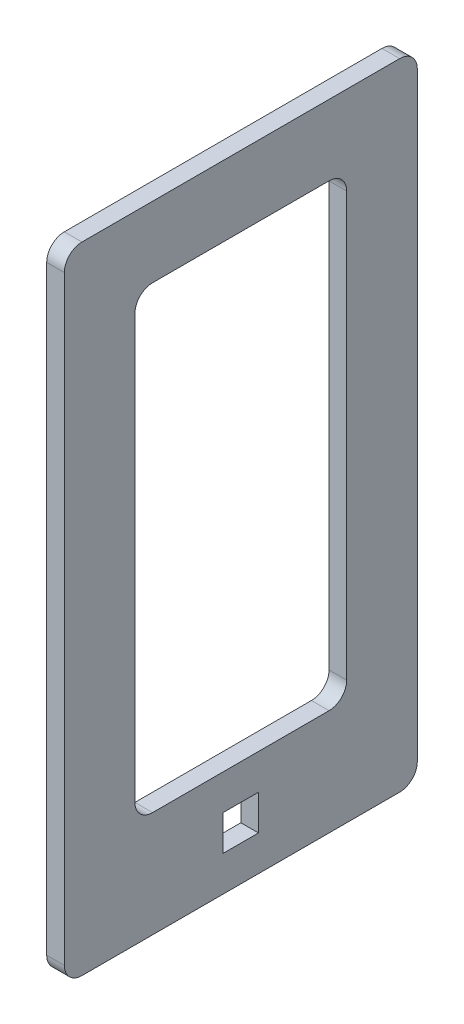
SolidWorks part; units mm, degrees
material "Balsa"
ref_plane "Front Plane" through (0, 0, 0) normal (0, 0, 1) x (1, 0, 0)
ref_plane "Top Plane" through (0, 0, 0) normal (0, 1, 0) x (1, 0, 0)
ref_plane "Right Plane" through (0, 0, 0) normal (1, 0, 0) x (0, 0, -1)
sketch "Sketch3" plane through (0, 0, 0) normal (1, 0, 0) x (0, 0, -1)
  line L0 (-31.75, -76.2) -> (31.75, -76.2)
  line L1 (-57.15, -114.3) -> (57.15, -114.3)
  line L2 (-63.5, -107.95) -> (-63.5, 107.95)
  line L3 (-57.15, 114.3) -> (57.15, 114.3)
  line L4 (63.5, -107.95) -> (63.5, 107.95)
  line L5 (-63.5, -114.3) -> (63.5, 114.3) construction
  line L6 (-63.5, 114.3) -> (63.5, -114.3) construction
  line L8 (-38.1, -69.85) -> (-38.1, 82.55)
  line L9 (-31.75, 88.9) -> (31.75, 88.9)
  line L11 (0, 0) -> (38.1, 88.9) construction
  line L12 (-38.1, 88.9) -> (0, 0) construction
  line L13 (38.1, -69.85) -> (38.1, 82.55)
  arc A0 (-57.15, -114.3) -> (-63.5, -107.95) centre (-57.15, -107.95) cw
  arc A1 (63.5, -107.95) -> (57.15, -114.3) centre (57.15, -107.95) cw
  arc A2 (63.5, 107.95) -> (57.15, 114.3) centre (57.15, 107.95) ccw
  arc A3 (-63.5, 107.95) -> (-57.15, 114.3) centre (-57.15, 107.95) cw
  arc A4 (31.75, -76.2) -> (38.1, -69.85) centre (31.75, -69.85) ccw
  arc A5 (-31.75, -76.2) -> (-38.1, -69.85) centre (-31.75, -69.85) cw
  arc A6 (31.75, 88.9) -> (38.1, 82.55) centre (31.75, 82.55) cw
  arc A7 (-38.1, 82.55) -> (-31.75, 88.9) centre (-31.75, 82.55) cw
  point P0 (0, 0)
  point P6 (0, 0)
  point P26 (38.1, -76.2)
  dimension "D7" = 6.35
  dimension "D8" = 6.35
  dimension "D1" = 228.6
  dimension "D2" = 127
  dimension "D3" = 76.2
  dimension "D4" = 165.1
  dimension "D5" = 25.4
  dimension "D6" = 25.4
extrude "Boss-Extrude2" add sketch "Sketch3" along normal blind 6.35
sketch "Sketch4" plane through (6.35, 0, 0) normal (1, 0, 0) x (0, 0, -1)
  line L0 (0, 55) -> (0, -55) construction
  line L1 (-6.35, -101.6) -> (6.35, -101.6)
  line L2 (-6.35, -101.6) -> (-6.35, -88.9)
  line L3 (-6.35, -88.9) -> (6.35, -88.9)
  line L4 (6.35, -101.6) -> (6.35, -88.9)
  line L5 (-6.35, -101.6) -> (6.35, -88.9) construction
  line L6 (-6.35, -88.9) -> (6.35, -101.6) construction
  line L7 (-57.15, -114.3) -> (57.15, -114.3) construction
  point P0 (0, -95.25)
  dimension "D1" = 12.7
  dimension "D2" = 12.7
  dimension "D3" = 12.7
extrude "Cut-Extrude1" cut sketch "Sketch4" against normal up to next
